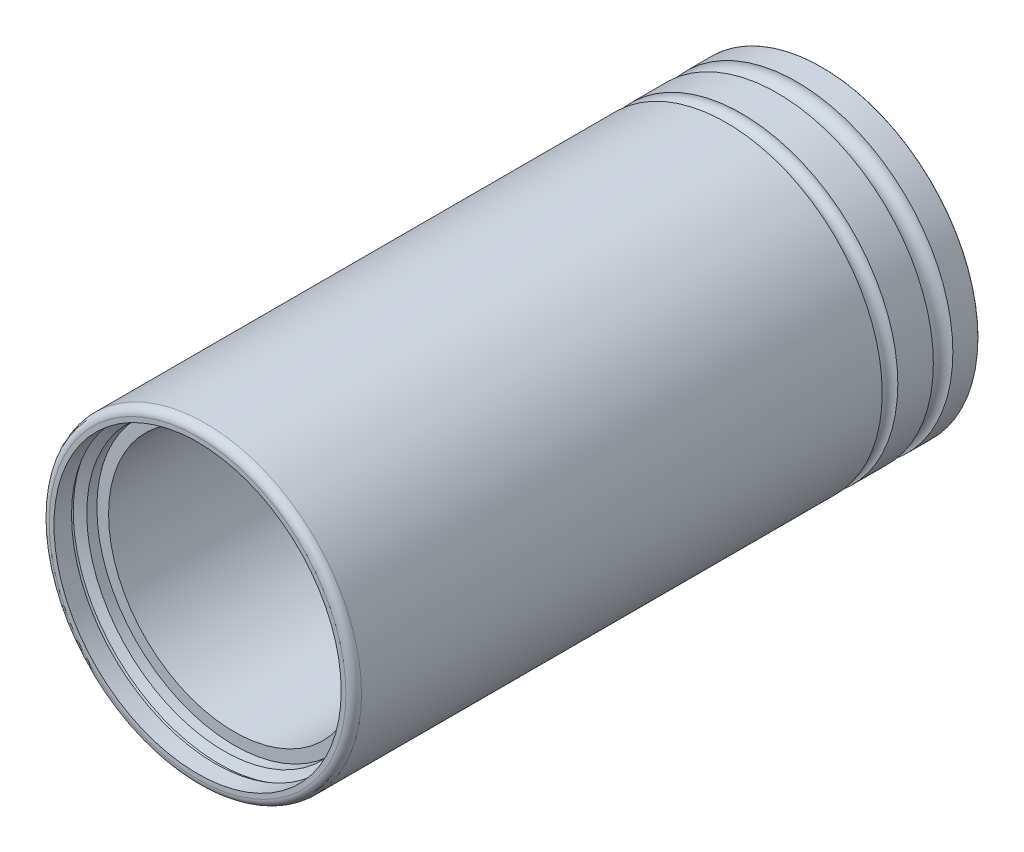
SolidWorks part; units mm, degrees
material "AISI 304"
ref_plane "Спереди" through (0, 0, 0) normal (0, 0, 1) x (1, 0, 0)
ref_plane "Сверху" through (0, 0, 0) normal (0, 1, 0) x (1, 0, 0)
ref_plane "Справа" through (0, 0, 0) normal (1, 0, 0) x (0, 0, -1)
sketch "Эскиз1" plane through (0, 0, 0) normal (0, 0, 1) x (1, 0, 0)
  circle A0 centre (0, 0) radius 20
  dimension "D1" = 40
extrude "Бобышка-Вытянуть1" add sketch "Эскиз1" against normal blind 80
sketch "Эскиз4" plane through (0, 0, 0) normal (1, 0, 0) x (0, 0, -1)
  line L0 (0, 0) -> (0, 17.6)
  line L1 (0, 20) -> (0, -20) construction
  line L2 (0, 17.6) -> (4.7, 17.6)
  line L3 (4.7, 17.6) -> (4.7, 16.1)
  line L4 (4.7, 16.1) -> (27, 16.1)
  line L8 (27, 16.1) -> (27, 17.1)
  line L9 (27, 17.1) -> (28.4, 17.1)
  line L14 (55, 6) -> (57, 6)
  line L15 (57, 6) -> (57, 9.5)
  line L16 (57, 9.5) -> (60.8, 9.5)
  line L20 (62, 9.5) -> (63.5, 9.5)
  line L21 (63.5, 9.5) -> (63.5, 10.75)
  line L22 (63.5, 10.75) -> (75, 10.75)
  line L23 (75, 10.75) -> (75, 12.4)
  line L24 (75, 12.4) -> (78, 12.4)
  line L25 (78, 12.4) -> (78, 10.75)
  line L26 (78, 10.75) -> (80, 10.75)
  line L27 (80, -20) -> (80, 20) construction
  line L28 (80, 10.75) -> (80, 0)
  line L29 (80, 0) -> (0, 0)
  line L52 (55, 6) -> (55, 16.2)
  line L53 (28.4, 17.1) -> (28.9196, 16.2)
  line L54 (28.9196, 16.2) -> (29.8, 16.2)
  line L55 (29.8, 16.2) -> (29.8, 17.7)
  line L56 (29.8, 17.7) -> (33.8, 17.7)
  line L57 (33.8, 17.7) -> (33.8, 16.2)
  line L58 (33.8, 16.2) -> (34.8, 16.2)
  line L59 (34.8, 16.2) -> (34.8, 17.9)
  line L60 (34.8, 17.9) -> (38, 17.9)
  line L61 (38, 17.9) -> (38, 16.2)
  line L62 (38, 16.2) -> (39, 16.2)
  line L63 (39, 16.2) -> (39, 17.7)
  line L64 (39, 17.7) -> (47.8, 17.7)
  line L65 (47.8, 17.7) -> (47.8, 16.2)
  line L66 (47.8, 16.2) -> (48.8, 16.2)
  line L67 (48.8, 16.2) -> (48.8, 17.9)
  line L68 (48.8, 17.9) -> (52, 17.9)
  line L69 (52, 17.9) -> (52, 16.2)
  line L70 (52, 16.2) -> (55, 16.2)
  arc A0 (60.8, 9.5) -> (62, 9.5) centre (61.4, 9.5) cw
  dimension "D8" = 0.6
  dimension "D1" = 10.75
  dimension "D2" = 12.4
  dimension "D3" = 2
  dimension "D4" = 3
  dimension "D5" = 16.5
  dimension "D6" = 2.1
  dimension "D7" = 9.5
  dimension "D9" = 17.1
  dimension "D10" = 2
  dimension "D11" = 60
  dimension "D12" = 17.6
  dimension "D13" = 16.2
  dimension "D14" = 4.7
  dimension "D15" = 29.8
  dimension "D16" = 4
  dimension "D17" = 16.1
  dimension "D18" = 6
  dimension "D19" = 1.4
  dimension "D20" = 23
  dimension "D21" = 27
  dimension "D22" = 17.7
  dimension "D23" = 5.2
  dimension "D24" = 8.8
  dimension "D25" = 34.8
  dimension "D26" = 3.2
  dimension "D27" = 10.8
  dimension "D28" = 3.2
  dimension "D29" = 17.9
revolve "Вырез-Повернуть1" cut sketch "Эскиз4" angle 360 about L29
sketch "Эскиз5" plane through (0, 0, 0) normal (1, 0, 0) x (0, 0, -1)
  line L0 (3.4083, 17.6) -> (1.7917, 17.6)
  line L1 (1.7917, 17.6) -> (2.6, 19)
  line L2 (2.6, 19) -> (3.4083, 17.6)
  line L3 (4.7, 17.6) -> (4.7, -17.6) construction
  line L4 (4.7, 17.6) -> (4.7, -17.6) construction
  line L5 (0, 17.6) -> (0, -17.6) construction
  line L6 (0, 0) -> (8.2655, 0) construction
  line L7 (0, 20) -> (0, -20) construction
  line L8 (0, 20) -> (0, -20) construction
  point P3 (2.6, 17.6)
  dimension "D1" = 1
  dimension "D2" = 60
  dimension "D3" = 2.6
revolve "Вырез-Повернуть2" cut sketch "Эскиз5" angle 360 about L6
fillet "Скругление2" radius 1 1 edges at (20, 0, 0)
sketch "Эскиз6" plane through (0, 0, 0) normal (0, 0, 1) x (1, 0, 0)
  circle A2 centre (0, 0) radius 18.4
  dimension "D1" = 36.8
extrude "Вырез-Вытянуть1" cut sketch "Эскиз6" against normal blind 2.6
fillet "Скругление3" radius 0.05 3 edges at (-10.75, 0, -80) (20, 0, -80) (-6, 0, -57)
fillet "Скругление4" [suppressed] radius 0.1
fillet "Скругление5" [suppressed] radius 0.2
fillet "Скругление6" [suppressed] radius 0.4
fillet "Скругление7" [suppressed] radius 0.2
sketch "Эскиз7" plane through (0, 0, 0) normal (0, 1, 0) x (1, 0, 0)
  line L0 (19.95, 80) -> (-19.95, 80) construction
  line L1 (-15.75, 80) -> (-13.25, 80)
  line L2 (0, 88.9589) -> (0, 57.4428) construction
  arc A0 (-15.75, 80) -> (-13.25, 80) centre (-14.5, 80) cw
  dimension "D1" = 1.25
  dimension "D2" = 14.5
revolve "Повернуть1" add sketch "Эскиз7" angle 360 about L2
sketch "Эскиз8" plane through (0, 0, 0) normal (1, 0, 0) x (0, 0, -1)
  line L0 (1, -20) -> (1, 20) construction
  line L1 (1, -20) -> (1, 20) construction
  line L2 (75.5, 20) -> (40.6285, 20) construction
  line L7 (0, 0) -> (74.6339, 0) construction
  line L8 (80, -19.95) -> (80, 19.95) construction
  line L9 (80, -19.95) -> (80, 19.95) construction
  line L10 (79.95, 20) -> (1, 20) construction
  circle A0 centre (75.5, 20) radius 1.25
  circle A1 centre (68.7, 20) radius 1
  dimension "D1" = 2.5
  dimension "D3" = 2
  dimension "D4" = 6.8
  dimension "D2" = 4.5
  dimension "D5" = 20
revolve "Вырез-Повернуть3" cut sketch "Эскиз8" angle 360 about L7
fillet "Скругление10" [suppressed] radius 0.2
fillet "Скругление11" [suppressed] radius 0.2
fillet "Скругление12" radius 0.4 4 edges at (-17.9, 0, -52) (-17.9, 0, -48.8) (-17.9, 0, -38) (-17.9, 0, -34.8)
fillet "Скругление13" radius 0.2 4 edges at (-16.2, 0, -52) (-16.2, 0, -48.8) (-16.2, 0, -38) (-16.2, 0, -34.8)
fillet "Скругление14" radius 0.2 2 edges at (-10.75, 0, -75) (-10.75, 0, -78)
fillet "Скругление15" radius 0.4 2 edges at (-12.4, 0, -78) (-12.4, 0, -75)
fillet "Скругление16" radius 0.2 1 edges at (19, 0, -2.6)
